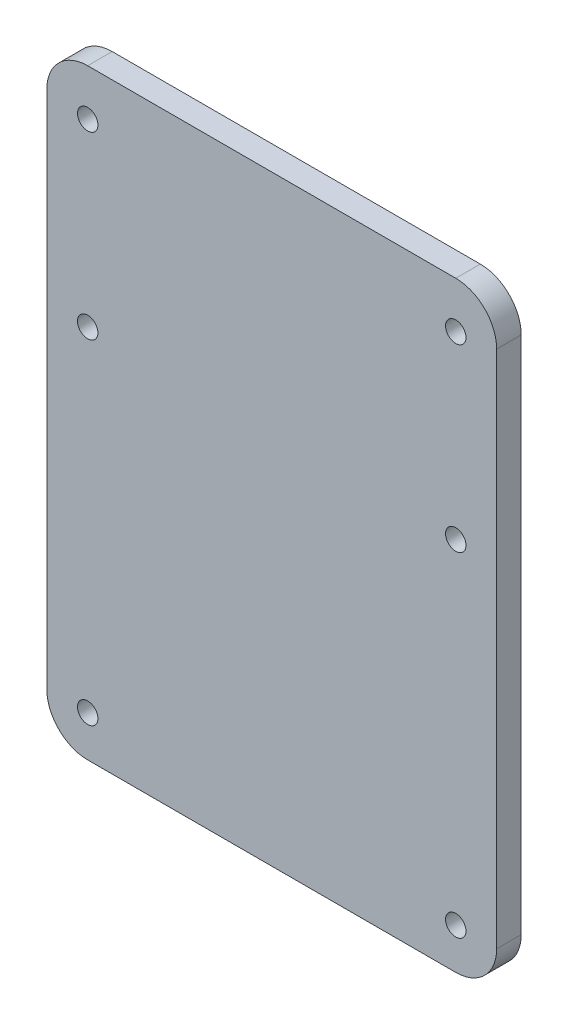
SolidWorks part; units mm, degrees
ref_plane "Front Plane" through (0, 0, 0) normal (0, 0, 1) x (1, 0, 0)
ref_plane "Top Plane" through (0, 0, 0) normal (0, 1, 0) x (1, 0, 0)
ref_plane "Right Plane" through (0, 0, 0) normal (1, 0, 0) x (0, 0, -1)
sketch "Sketch1" plane through (0, 0, 0) normal (0, 0, 1) x (1, 0, 0)
  line L1 (-25.7372, 42.2489) -> (29.2628, 42.2489)
  line L2 (-25.7372, 42.2489) -> (-25.7372, -31.2511)
  line L3 (-25.7372, -31.2511) -> (29.2628, -31.2511)
  line L4 (29.2628, 42.2489) -> (29.2628, -31.2511)
  dimension "D1" = 55
  dimension "D2" = 73.5
extrude "Boss-Extrude1" add sketch "Sketch1" along normal blind 3
sketch "Sketch2" plane through (0, 0, 3) normal (0, 0, 1) x (1, 0, 0)
  line L0 (-25.7372, 42.2489) -> (-25.7372, -31.2511) construction
  line L1 (-25.7372, -31.2511) -> (29.2628, -31.2511) construction
  circle A0 centre (-20.7372, 36.588) radius 1.25
  circle A1 centre (24.2628, 36.588) radius 1.25
  circle A2 centre (-20.7372, 14.588) radius 1.25
  circle A3 centre (24.2628, 14.588) radius 1.25
  circle A4 centre (-20.7372, -26.2511) radius 1.25
  circle A5 centre (24.2628, -26.2511) radius 1.25
  dimension "D3" = 2.5
  dimension "D4" = 2.5
  dimension "D6" = 2.5
  dimension "D7" = 2.5
  dimension "D8" = 2.5
  dimension "D9" = 2.5
  dimension "D1" = 45
  dimension "D2" = 5
  dimension "D5" = 22
  dimension "D10" = 5
extrude "Cut-Extrude1" cut sketch "Sketch2" against normal blind 3
fillet "Fillet1" radius 5 4 edges at (29.2628, -31.2511, 1.5) (-25.7372, -31.2511, 1.5) (-25.7372, 42.2489, 1.5) (29.2628, 42.2489, 1.5)
